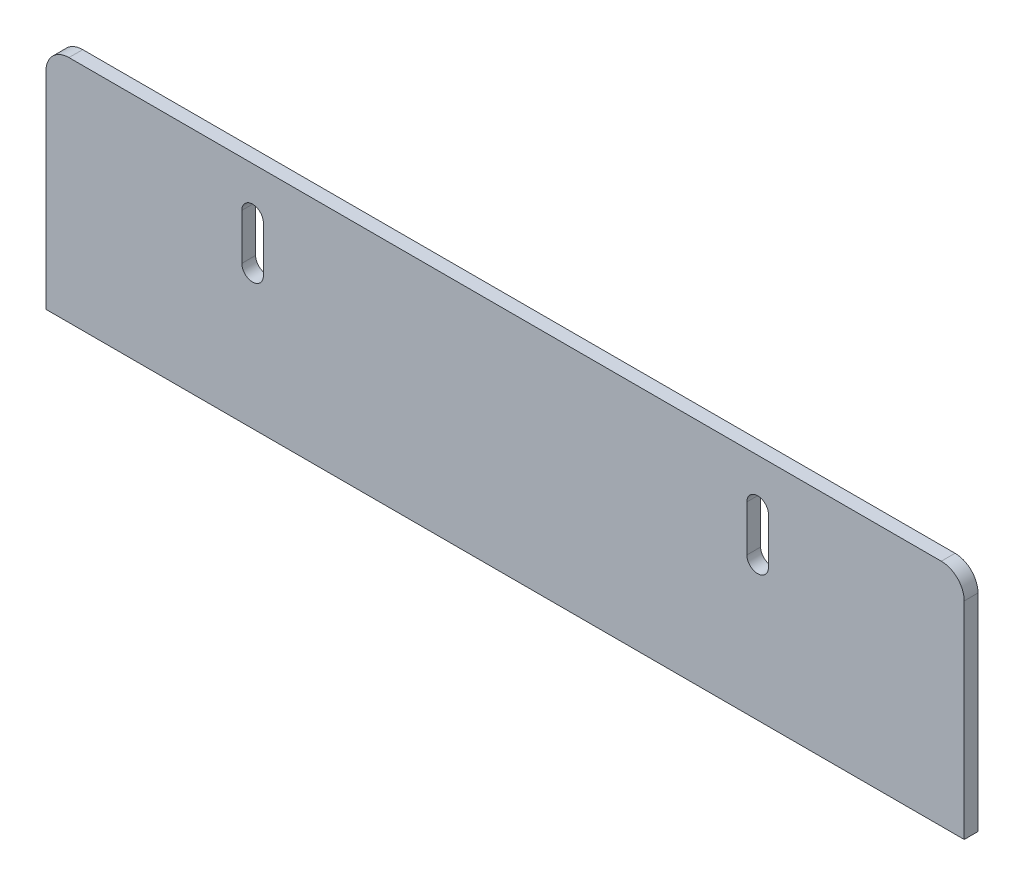
SolidWorks part; units mm, degrees
ref_plane "前视基准面" through (0, 0, 0) normal (0, 0, 1) x (1, 0, 0)
ref_plane "上视基准面" through (0, 0, 0) normal (0, 1, 0) x (1, 0, 0)
ref_plane "右视基准面" through (0, 0, 0) normal (1, 0, 0) x (0, 0, -1)
sketch "草图1" plane through (0, 0, 0) normal (0, 0, 1) x (1, 0, 0)
  line L0 (100, 50) -> (100, 0) construction
  line L1 (0, 0) -> (200, 0)
  line L2 (0, 0) -> (0, 45)
  line L3 (5, 50) -> (195, 50)
  line L4 (200, 0) -> (200, 45)
  line L5 (42.649, 40) -> (42.649, 30)
  line L6 (47.351, 40) -> (47.351, 30)
  line L7 (152.649, 40) -> (152.649, 30)
  line L8 (157.351, 40) -> (157.351, 30)
  arc A0 (47.351, 40) -> (42.649, 40) centre (45, 40) ccw
  arc A1 (42.649, 30) -> (47.351, 30) centre (45, 30) ccw
  arc A2 (157.351, 30) -> (152.649, 30) centre (155, 30) cw
  arc A3 (152.649, 40) -> (157.351, 40) centre (155, 40) cw
  arc A4 (200, 45) -> (195, 50) centre (195, 45) ccw
  arc A5 (0, 45) -> (5, 50) centre (5, 45) cw
  dimension "D1" = 55
  dimension "D3" = 5
  dimension "D2" = 10
  dimension "D4" = 200
  dimension "D6" = 50
  dimension "D7" = 10
extrude "凸台-拉伸1" add sketch "草图1" along normal blind 3
